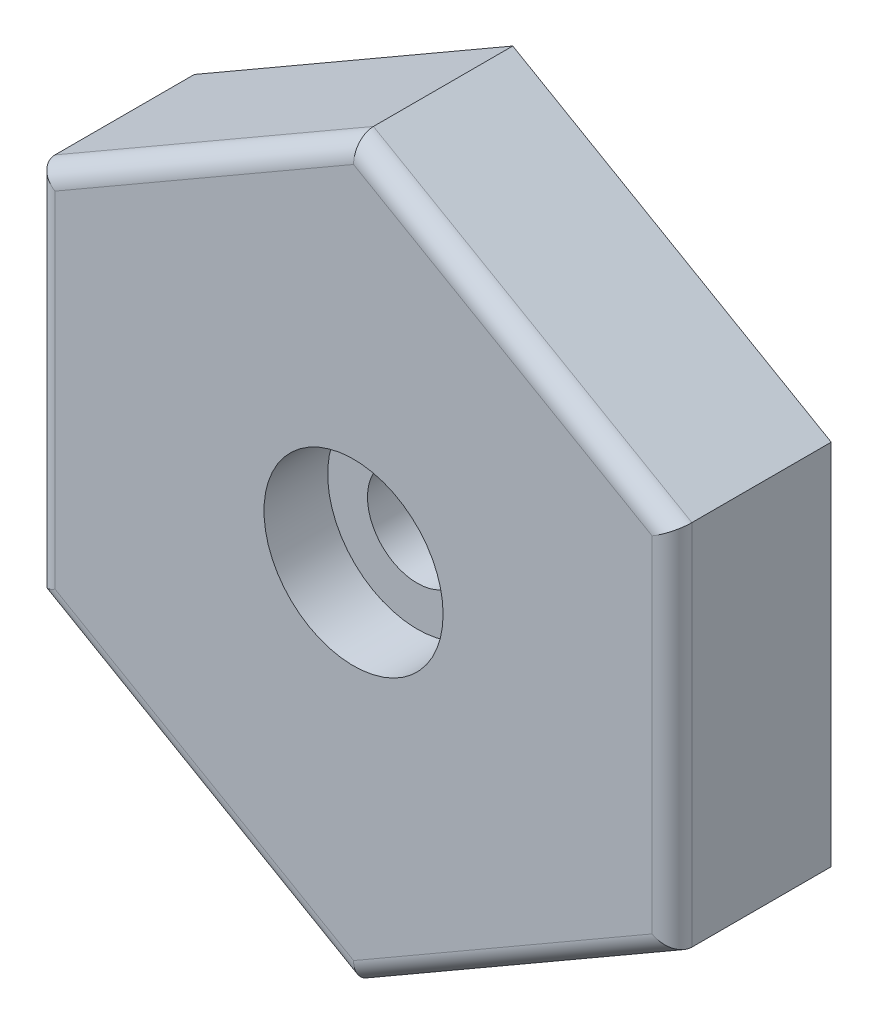
SolidWorks part; units mm, degrees
ref_plane "Ebene vorne" through (0, 0, 0) normal (0, 0, 1) x (1, 0, 0)
ref_plane "Ebene oben" through (0, 0, 0) normal (0, 1, 0) x (1, 0, 0)
ref_plane "Ebene rechts" through (0, 0, 0) normal (1, 0, 0) x (0, 0, -1)
sketch "Skizze1" plane through (0, 0, 0) normal (0, 0, 1) x (1, 0, 0)
  line L1 (16, 9.2376) -> (0, 18.4752)
  line L2 (0, 18.4752) -> (-16, 9.2376)
  line L3 (-16, 9.2376) -> (-16, -9.2376)
  line L4 (-16, -9.2376) -> (0, -18.4752)
  line L5 (0, -18.4752) -> (16, -9.2376)
  line L6 (16, -9.2376) -> (16, 9.2376)
  circle A0 centre (0, 0) radius 16 construction
  circle A1 centre (0, 0) radius 2.5
extrude "Aufsatz-Linear austragen1" add sketch "Skizze1" along normal blind 8
sketch "Skizze2" plane through (0, 0, 8) normal (0, 0, 1) x (1, 0, 0)
  circle A0 centre (0, 0) radius 4.5
extrude "Schnitt-Linear austragen1" cut sketch "Skizze2" against normal blind 3.2
sketch "Skizze3" plane through (0, 0, 0) normal (0, 0, -1) x (-1, 0, 0)
  line L1 (13.9719, 0) -> (6.9859, 12.1)
  line L2 (6.9859, 12.1) -> (-6.9859, 12.1)
  line L3 (-6.9859, 12.1) -> (-13.9719, 0)
  line L4 (-13.9719, 0) -> (-6.9859, -12.1)
  line L5 (-6.9859, -12.1) -> (6.9859, -12.1)
  line L6 (6.9859, -12.1) -> (13.9719, 0)
  circle A0 centre (0, 0) radius 12.1 construction
  circle A1 centre (0, 0) radius 8
extrude "Schnitt-Linear austragen2" cut sketch "Skizze3" against normal blind 6
fillet "Verrundung1" radius 1 6 edges at (-8, 13.8564, 8) (-16, 0, 8) (-8, -13.8564, 8) (8, -13.8564, 8) (16, 0, 8) (8, 13.8564, 8)
sketch "Skizze10" plane through (0, 0, 0) normal (0, 0, -1) x (-1, 0, 0)
  circle A0 centre (0, 0) radius 8
extrude "Schnitt-Linear austragen3" cut sketch "Skizze10" against normal blind 2
